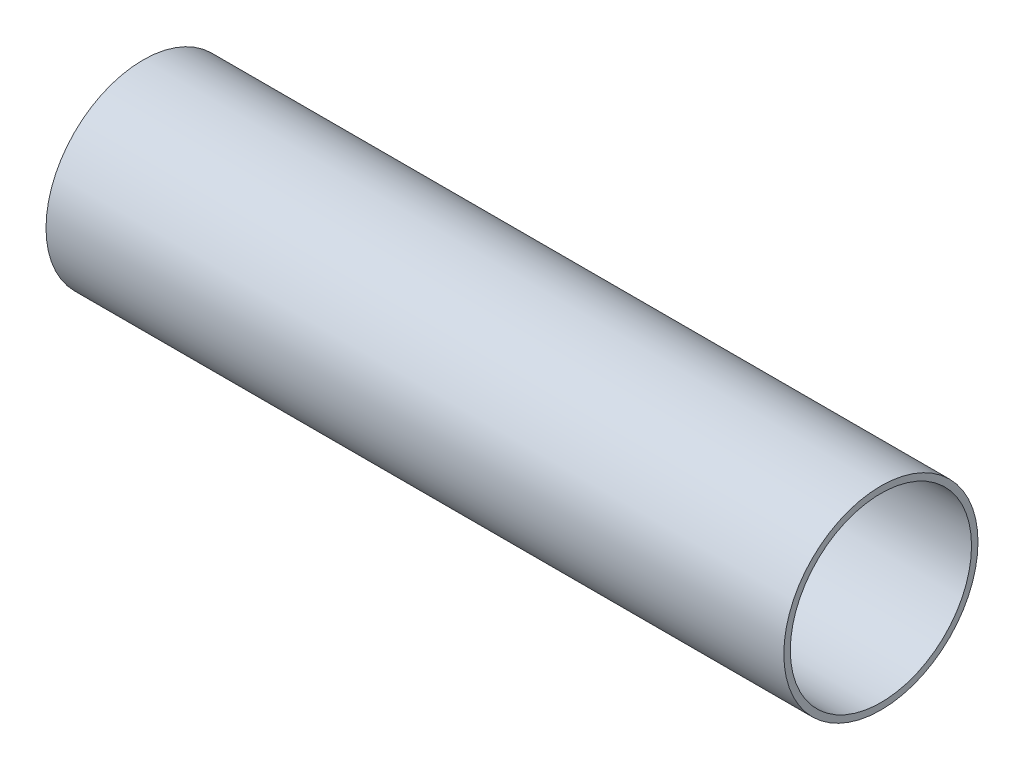
SolidWorks part; units mm, degrees
ref_plane "Płaszczyzna przednia" through (0, 0, 0) normal (0, 0, 1) x (1, 0, 0)
ref_plane "Płaszczyzna górna" through (0, 0, 0) normal (0, 1, 0) x (1, 0, 0)
ref_plane "Płaszczyzna prawa" through (0, 0, 0) normal (1, 0, 0) x (0, 0, -1)
sketch "Szkic1" plane through (0, 0, 0) normal (0, 0, 1) x (1, 0, 0)
  line L0 (0, 0) -> (105558.8307, 0) construction
  line L1 (-158.6842, 75) -> (411.3158, 75)
  line L2 (-158.6842, 75) -> (-158.6842, 0)
  line L3 (411.3158, 75) -> (411.3158, 0)
  line L4 (-158.6842, 70) -> (411.3158, 70)
  dimension "D1" = 150
  dimension "D2" = 140
  dimension "D3" = 570
revolve "Obrót1" add sketch "Szkic1" angle 360 about L0
